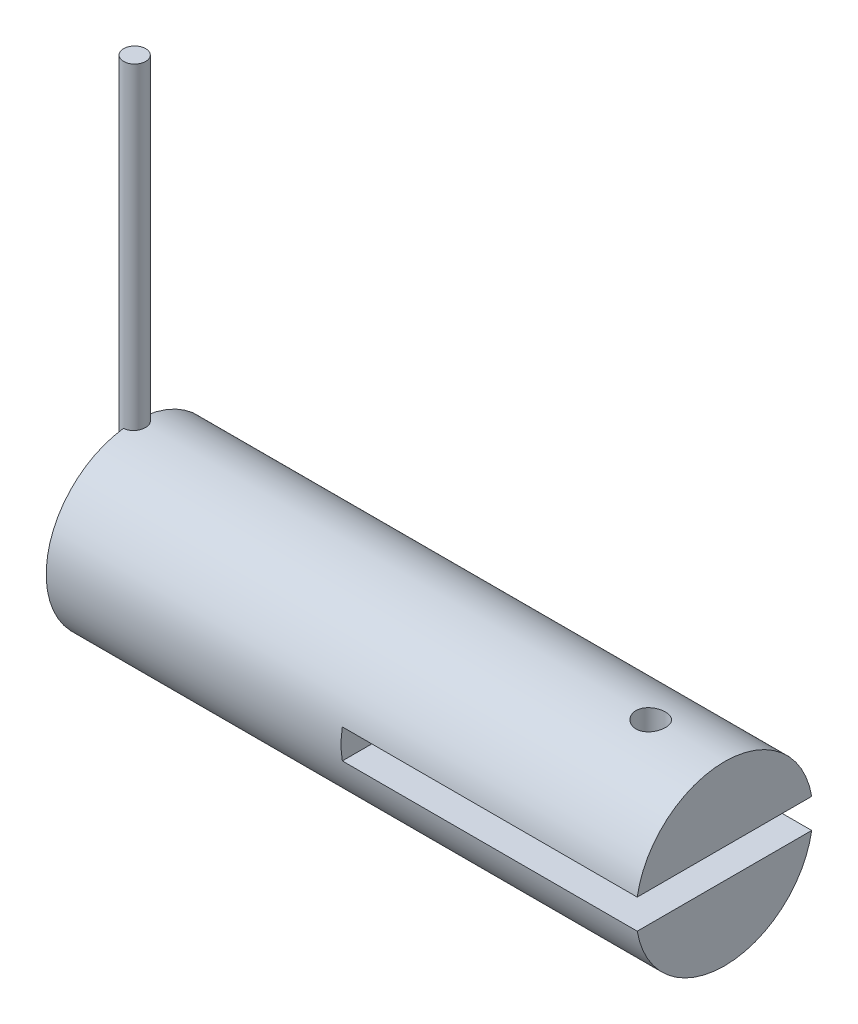
SolidWorks part; units mm, degrees
ref_plane "前视基准面" through (0, 0, 0) normal (0, 0, 1) x (1, 0, 0)
ref_plane "上视基准面" through (0, 0, 0) normal (0, 1, 0) x (1, 0, 0)
ref_plane "右视基准面" through (0, 0, 0) normal (1, 0, 0) x (0, 0, -1)
other "Configuration Table"
sketch "草图1" plane through (0, 0, 0) normal (0, 1, 0) x (1, 0, 0)
  circle A0 centre (0, 0) radius 1.5
extrude "凸台-拉伸1" add sketch "草图1" along normal blind 55
sketch "草图2" plane through (0, 0, 0) normal (1, 0, 0) x (0, 0, -1)
  circle A0 centre (0, 0) radius 12
  dimension "D1" = 24
extrude "凸台-拉伸2" add sketch "草图2" along normal blind 80
sketch "草图4" plane through (80, 0, 0) normal (1, 0, 0) x (0, 0, -1)
  line L0 (-10.9087, -2) -> (-11.8322, -2)
  line L1 (-11.8322, 2) -> (11.8322, 2)
  line L2 (-6.5628, 1.5741) -> (-6.7124, 2)
  line L3 (-10.9087, -2) -> (10.9087, -2)
  line L4 (10.9087, -2) -> (11.8322, -2)
  circle A0 centre (0, 0) radius 12 construction
  circle A1 centre (0, 0) radius 12
  dimension "D1" = 4
  dimension "D2" = 2
extrude "切除-拉伸1" cut sketch "草图4" against normal blind 40
sketch "草图5" plane through (0, 2, 0) normal (0, -1, 0) x (1, 0, 0)
  line L0 (80, -11.8322) -> (80, 11.8322) construction
  circle A0 centre (70, 0) radius 2
  dimension "D1" = 10
extrude "切除-拉伸2" cut sketch "草图5" against normal through all and the other way through all
sketch "草图6" plane through (0, 55, 0) normal (0, 1, 0) x (1, 0, 0)
  line L0 (0, 0) -> (0, 1.5)
  line L1 (0, 0) -> (-1.5, 0)
  circle A0 centre (0, 0) radius 1.5 construction
sketch "草图9" plane through (0, 0, 0) normal (-1, 0, 0) x (0, 0, 1)
  point P0 (0, 0)
